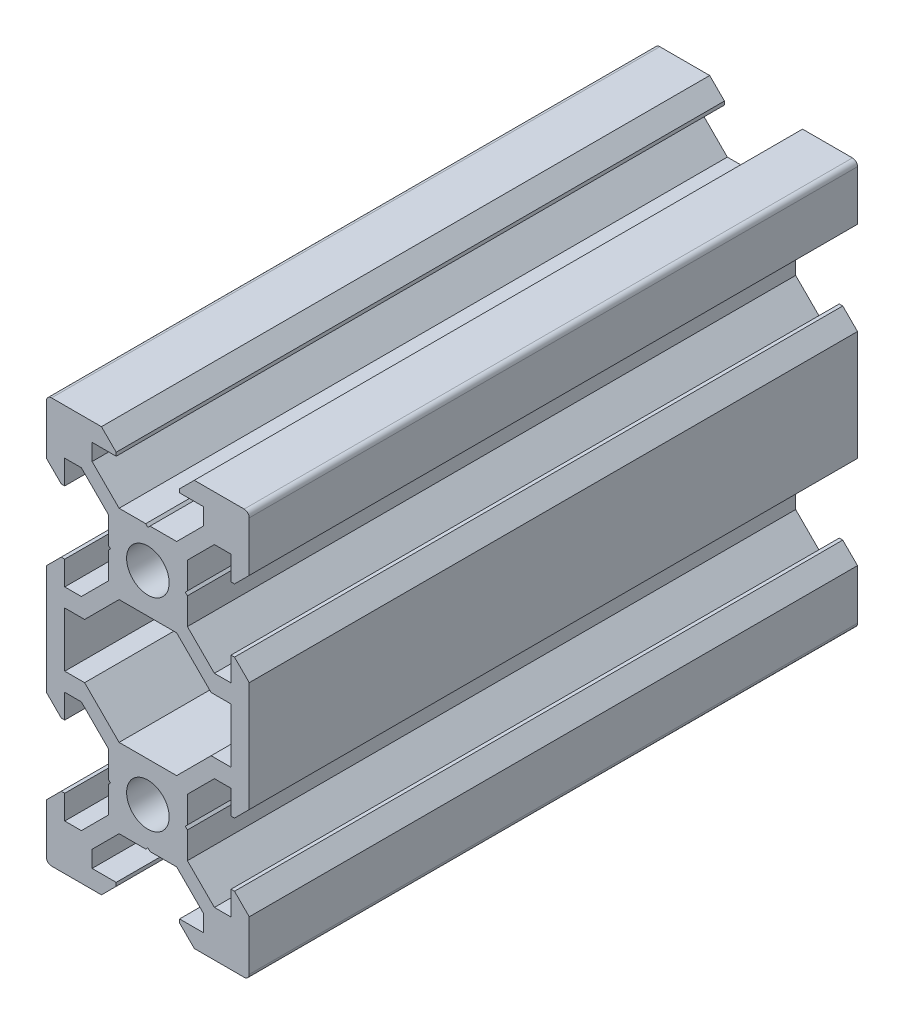
SolidWorks part; units mm, degrees
material "6061-T6 (SS)"
ref_plane "Front Plane" through (0, 0, 0) normal (0, 0, 1) x (1, 0, 0)
ref_plane "Top Plane" through (0, 0, 0) normal (0, 1, 0) x (1, 0, 0)
ref_plane "Right Plane" through (0, 0, 0) normal (1, 0, 0) x (0, 0, -1)
sketch "Sketch1" plane through (0, 0, 0) normal (0, 0, 1) x (1, 0, 0)
  line L0 (0, 0) -> (10, 0) construction
  line L1 (9.5, -20) -> (-9.5, -20)
  line L2 (10, -19.5) -> (10, 19.5)
  line L3 (9.5, 20) -> (-9.5, 20)
  line L4 (-10, -19.5) -> (-10, 19.5)
  line L5 (10, -20) -> (-10, 20) construction
  line L6 (10, 20) -> (-10, -20) construction
  circle A0 centre (0, 10) radius 2.1
  circle A1 centre (0, -10) radius 2.1
  arc A2 (-9.5, -20) -> (-10, -19.5) centre (-9.5, -19.5) cw
  arc A3 (9.5, -20) -> (10, -19.5) centre (9.5, -19.5) ccw
  arc A4 (10, 19.5) -> (9.5, 20) centre (9.5, 19.5) ccw
  arc A5 (-9.5, 20) -> (-10, 19.5) centre (-9.5, 19.5) ccw
  point P0 (0, 0)
  line B0 (0, 10) -> (0, 20) construction
  line B1 (0, 13.69) -> (-0.21, 13.9)
  line B2 (-0.21, 13.9) -> (-2.8393, 13.9)
  line B3 (-2.8393, 13.9) -> (-5.5, 16.5607)
  line B4 (-5.5, 16.5607) -> (-5.5, 18.2)
  line B5 (-5.5, 18.2) -> (-3.125, 18.2)
  line B6 (-3.125, 18.2) -> (-3.125, 18.545)
  line B7 (-3.125, 18.545) -> (-4.58, 20)
  line B8 (-4.58, 20) -> (4.58, 20)
  line B9 (0, 10) -> (-5.9132, 15.9132) construction
  line B10 (3.125, 18.545) -> (4.58, 20)
  line B11 (3.125, 18.2) -> (3.125, 18.545)
  line B12 (5.5, 18.2) -> (3.125, 18.2)
  line B13 (5.5, 16.5607) -> (5.5, 18.2)
  line B14 (2.8393, 13.9) -> (5.5, 16.5607)
  line B15 (0.21, 13.9) -> (2.8393, 13.9)
  line B16 (0, 13.69) -> (0.21, 13.9)
  line B17 (0, 10) -> (-10, 10) construction
  line B18 (-3.69, 10) -> (-3.9, 9.79)
  line B19 (-3.9, 9.79) -> (-3.9, 7.1607)
  line B20 (-3.9, 7.1607) -> (-6.5607, 4.5)
  line B21 (-6.5607, 4.5) -> (-8.2, 4.5)
  line B22 (-8.2, 4.5) -> (-8.2, 6.875)
  line B23 (-8.2, 6.875) -> (-8.545, 6.875)
  line B24 (-8.545, 6.875) -> (-10, 5.42)
  line B25 (-10, 5.42) -> (-10, 14.58)
  line B26 (0, 10) -> (-5.9132, 4.0868) construction
  line B27 (-8.545, 13.125) -> (-10, 14.58)
  line B28 (-8.2, 13.125) -> (-8.545, 13.125)
  line B29 (-8.2, 15.5) -> (-8.2, 13.125)
  line B30 (-6.5607, 15.5) -> (-8.2, 15.5)
  line B31 (-3.9, 12.8393) -> (-6.5607, 15.5)
  line B32 (-3.9, 10.21) -> (-3.9, 12.8393)
  line B33 (-3.69, 10) -> (-3.9, 10.21)
  line B34 (0, -10) -> (-10, -10) construction
  line B35 (-3.69, -10) -> (-3.9, -10.21)
  line B36 (-3.9, -10.21) -> (-3.9, -12.8393)
  line B37 (-3.9, -12.8393) -> (-6.5607, -15.5)
  line B38 (-6.5607, -15.5) -> (-8.2, -15.5)
  line B39 (-8.2, -15.5) -> (-8.2, -13.125)
  line B40 (-8.2, -13.125) -> (-8.545, -13.125)
  line B41 (-8.545, -13.125) -> (-10, -14.58)
  line B42 (-10, -14.58) -> (-10, -5.42)
  line B43 (0, -10) -> (-5.9132, -15.9132) construction
  line B44 (-8.545, -6.875) -> (-10, -5.42)
  line B45 (-8.2, -6.875) -> (-8.545, -6.875)
  line B46 (-8.2, -4.5) -> (-8.2, -6.875)
  line B47 (-6.5607, -4.5) -> (-8.2, -4.5)
  line B48 (-3.9, -7.1607) -> (-6.5607, -4.5)
  line B49 (-3.9, -9.79) -> (-3.9, -7.1607)
  line B50 (-3.69, -10) -> (-3.9, -9.79)
  line B51 (0, -10) -> (0, -20) construction
  line B52 (0, -13.69) -> (0.21, -13.9)
  line B53 (0.21, -13.9) -> (2.8393, -13.9)
  line B54 (2.8393, -13.9) -> (5.5, -16.5607)
  line B55 (5.5, -16.5607) -> (5.5, -18.2)
  line B56 (5.5, -18.2) -> (3.125, -18.2)
  line B57 (3.125, -18.2) -> (3.125, -18.545)
  line B58 (3.125, -18.545) -> (4.58, -20)
  line B59 (4.58, -20) -> (-4.58, -20)
  line B60 (0, -10) -> (5.9132, -15.9132) construction
  line B61 (-3.125, -18.545) -> (-4.58, -20)
  line B62 (-3.125, -18.2) -> (-3.125, -18.545)
  line B63 (-5.5, -18.2) -> (-3.125, -18.2)
  line B64 (-5.5, -16.5607) -> (-5.5, -18.2)
  line B65 (-2.8393, -13.9) -> (-5.5, -16.5607)
  line B66 (-0.21, -13.9) -> (-2.8393, -13.9)
  line B67 (0, -13.69) -> (-0.21, -13.9)
  line B68 (0, -10) -> (10, -10) construction
  line B69 (3.69, -10) -> (3.9, -9.79)
  line B70 (3.9, -9.79) -> (3.9, -7.1607)
  line B71 (3.9, -7.1607) -> (6.5607, -4.5)
  line B72 (6.5607, -4.5) -> (8.2, -4.5)
  line B73 (8.2, -4.5) -> (8.2, -6.875)
  line B74 (8.2, -6.875) -> (8.545, -6.875)
  line B75 (8.545, -6.875) -> (10, -5.42)
  line B76 (10, -5.42) -> (10, -14.58)
  line B77 (0, -10) -> (5.9132, -4.0868) construction
  line B78 (8.545, -13.125) -> (10, -14.58)
  line B79 (8.2, -13.125) -> (8.545, -13.125)
  line B80 (8.2, -15.5) -> (8.2, -13.125)
  line B81 (6.5607, -15.5) -> (8.2, -15.5)
  line B82 (3.9, -12.8393) -> (6.5607, -15.5)
  line B83 (3.9, -10.21) -> (3.9, -12.8393)
  line B84 (3.69, -10) -> (3.9, -10.21)
  line B85 (0, 10) -> (10, 10) construction
  line B86 (3.69, 10) -> (3.9, 10.21)
  line B87 (3.9, 10.21) -> (3.9, 12.8393)
  line B88 (3.9, 12.8393) -> (6.5607, 15.5)
  line B89 (6.5607, 15.5) -> (8.2, 15.5)
  line B90 (8.2, 15.5) -> (8.2, 13.125)
  line B91 (8.2, 13.125) -> (8.545, 13.125)
  line B92 (8.545, 13.125) -> (10, 14.58)
  line B93 (10, 14.58) -> (10, 5.42)
  line B94 (0, 10) -> (5.9132, 15.9132) construction
  line B95 (8.545, 6.875) -> (10, 5.42)
  line B96 (8.2, 6.875) -> (8.545, 6.875)
  line B97 (8.2, 4.5) -> (8.2, 6.875)
  line B98 (6.5607, 4.5) -> (8.2, 4.5)
  line B99 (3.9, 7.1607) -> (6.5607, 4.5)
  line B100 (3.9, 9.79) -> (3.9, 7.1607)
  line B101 (3.69, 10) -> (3.9, 9.79)
  line B102 (-8.2, -2.7) -> (-8.2, 2.7)
  line B103 (-8.2, 2.7) -> (-6.2393, 2.7)
  line B104 (-6.2393, 2.7) -> (-2.8393, 6.1)
  line B105 (-2.8393, 6.1) -> (2.8393, 6.1)
  line B106 (0, 6.1) -> (0, 0) construction
  line B107 (0, 0) -> (-8.2, 0) construction
  line B108 (6.2393, 2.7) -> (2.8393, 6.1)
  line B109 (8.2, 2.7) -> (6.2393, 2.7)
  line B110 (8.2, -2.7) -> (8.2, 2.7)
  line B111 (8.2, -2.7) -> (6.2393, -2.7)
  line B112 (6.2393, -2.7) -> (2.8393, -6.1)
  line B113 (-2.8393, -6.1) -> (2.8393, -6.1)
  line B114 (-6.2393, -2.7) -> (-2.8393, -6.1)
  line B115 (-8.2, -2.7) -> (-6.2393, -2.7)
  line B116 (0, 6.1) -> (0, 10) construction
  line B117 (0, 10) -> (-5.0927, 4.9073) construction
  dimension "D4" = 4.2
  dimension "D5" = 0.5
  dimension "D1" = 20
  dimension "D2" = 40
  dimension "D3" = 20
sketch_block_instance "V Slot 1-4"
sketch_block "V Slot 1" parameters "D1"=10, "D2"=11, "D3"=4.3, "D4"=1.8, "D5"=0.21, "D6"=45, "D7"=9.16, "D8"=1.5, "D9"=6.25
sketch_block_instance "V Slot 1-5"
sketch_block_instance "V Slot 1-6"
sketch_block_instance "V Slot 1-7"
sketch_block_instance "V Slot 1-8"
sketch_block_instance "V Slot 1-9"
sketch_block_instance "Center Cutout 1-1"
sketch_block "Center Cutout 1" parameters "D1"=5.4, "D2"=12.2, "D3"=8.2, "D4"=45, "D5"=10, "D6"=1.5
extrude "Boss-Extrude1" add sketch "Sketch1" along normal blind 60 contours B101 B86 B87 B88 B89 B90 B91 B92 L2 A4 L3 B10 B11 B12 B13 B14 B15 B16 B1 B2 B3 B4 B5 B6 B7 A5 L4 B27 B28 B29 B30 B31 B32 B33 B18 B19 B20 B21 B22 B23 B24 B44 B45 B46 B47 B48 B49 B50 B35
